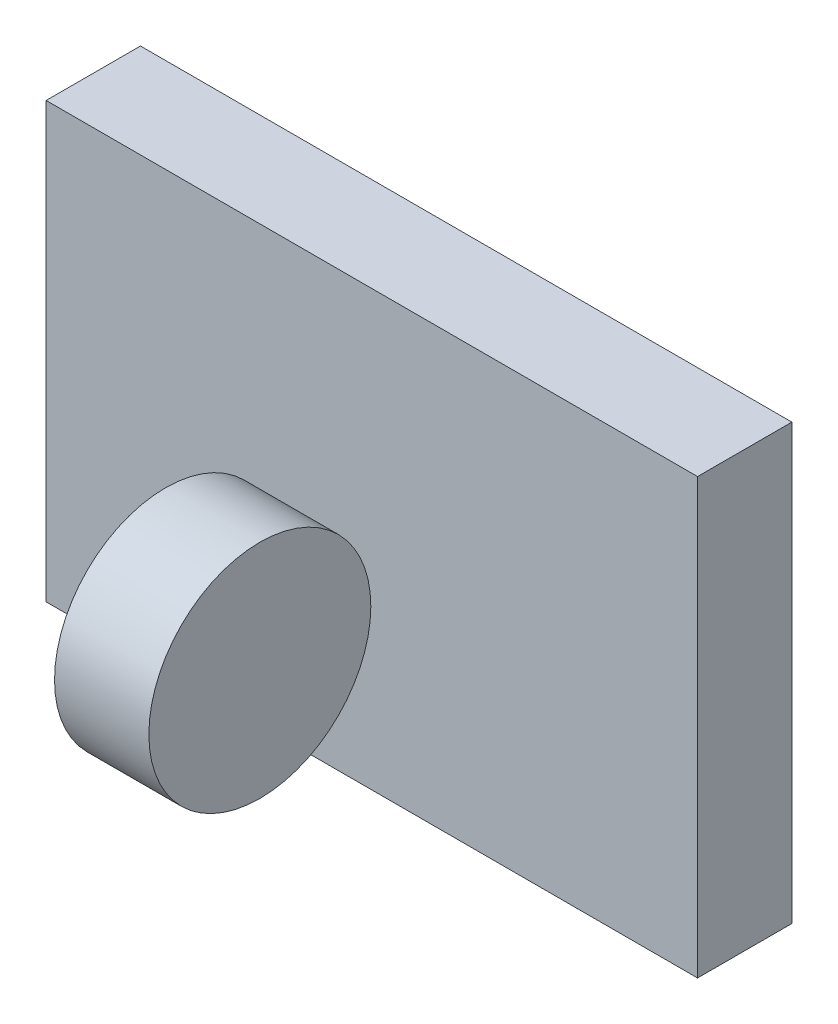
SolidWorks part; units mm, degrees
ref_plane "Спереди" through (0, 0, 0) normal (0, 0, 1) x (1, 0, 0)
ref_plane "Сверху" through (0, 0, 0) normal (0, 1, 0) x (1, 0, 0)
ref_plane "Справа" through (0, 0, 0) normal (1, 0, 0) x (0, 0, -1)
sketch "Эскиз1" plane through (0, 0, 0) normal (0, 0, 1) x (1, 0, 0)
  line L1 (-32.4073, 21.2507) -> (36.6575, 21.2507)
  line L2 (-32.4073, 21.2507) -> (-32.4073, -24.7925)
  line L3 (-32.4073, -24.7925) -> (36.6575, -24.7925)
  line L4 (36.6575, 21.2507) -> (36.6575, -24.7925)
extrude "Бобышка-Вытянуть1" add sketch "Эскиз1" against normal blind 10
sketch "Эскиз2" plane through (0, 0, 0) normal (1, 0, 0) x (0, 0, -1)
  circle A0 centre (-19.75, 0) radius 11.7674
  point P3 (-19.75, 0)
extrude "Бобышка-Вытянуть3" add sketch "Эскиз2" along normal blind 10 separate body
